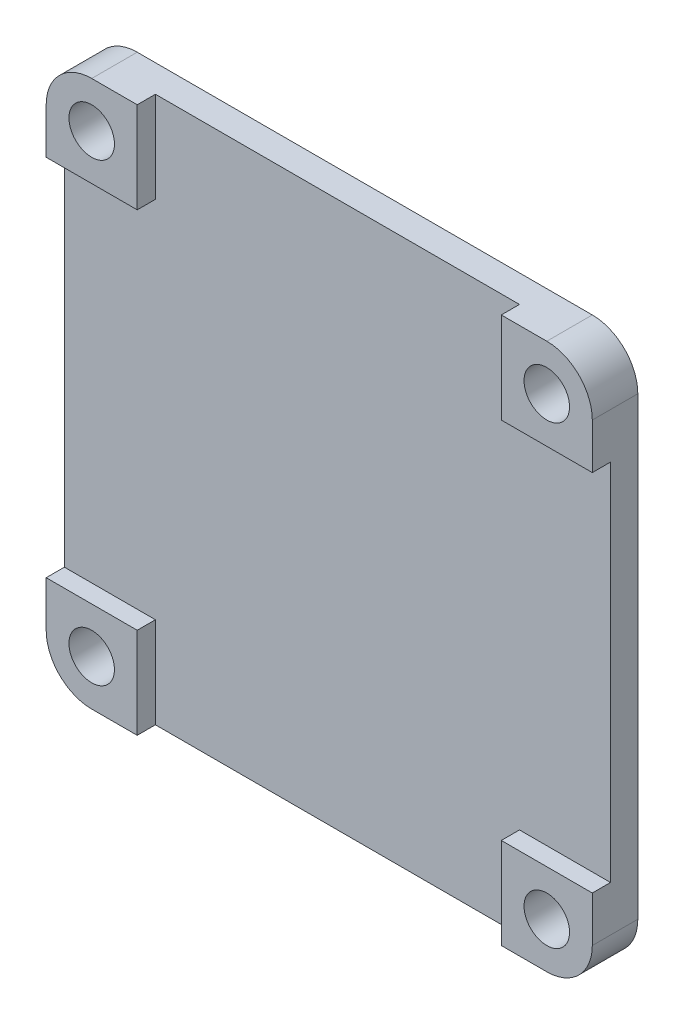
SolidWorks part; units mm, degrees
ref_plane "前视基准面" through (0, 0, 0) normal (0, 0, 1) x (1, 0, 0)
ref_plane "上视基准面" through (0, 0, 0) normal (0, 1, 0) x (1, 0, 0)
ref_plane "右视基准面" through (0, 0, 0) normal (1, 0, 0) x (0, 0, -1)
sketch "草图1" plane through (0, 0, 0) normal (0, 0, 1) x (1, 0, 0)
  line L0 (0, 0) -> (50.902, 0) construction
  line L1 (0, 0) -> (0, 39.4902) construction
  line L2 (-25, 30) -> (25, 30)
  line L3 (-30, 25) -> (-30, -25)
  line L4 (30, 25) -> (30, -25)
  line L5 (-25, -30) -> (25, -30)
  arc A0 (-25, 30) -> (-30, 25) centre (-25, 25) ccw
  circle A1 centre (-25, 25) radius 2.5
  circle A2 centre (25, 25) radius 2.5
  arc A3 (25, 30) -> (30, 25) centre (25, 25) cw
  arc A4 (25, -30) -> (30, -25) centre (25, -25) ccw
  circle A5 centre (25, -25) radius 2.5
  circle A6 centre (-25, -25) radius 2.5
  arc A7 (-25, -30) -> (-30, -25) centre (-25, -25) cw
  point P9 (0, -30)
  point P14 (-30, 0)
  point P15 (0, 30)
  point P23 (30, 0)
  dimension "D3" = 5
  dimension "D4" = 5
  dimension "D1" = 30
  dimension "D2" = 30
extrude "凸台-拉伸1" add sketch "草图1" along normal blind 3
sketch "草图2" plane through (0, 0, 3) normal (0, 0, 1) x (1, 0, 0)
  line L0 (0, 0) -> (46.7376, 0) construction
  line L1 (0, 0) -> (0, 23.4766) construction
  line L2 (-30, 25) -> (-30, 20)
  line L3 (-30, 25) -> (-30, -25) construction
  line L4 (-30, 20) -> (-20, 20)
  line L5 (-20, 20) -> (-20, 30)
  line L6 (25, 30) -> (-25, 30) construction
  line L7 (-20, 30) -> (-25, 30)
  line L8 (20, 30) -> (25, 30)
  line L9 (20, 20) -> (20, 30)
  line L10 (30, 20) -> (20, 20)
  line L11 (30, 25) -> (30, 20)
  line L12 (30, -25) -> (30, -20)
  line L13 (30, -20) -> (20, -20)
  line L14 (20, -20) -> (20, -30)
  line L15 (20, -30) -> (25, -30)
  line L16 (-20, -30) -> (-25, -30)
  line L17 (-20, -20) -> (-20, -30)
  line L18 (-30, -20) -> (-20, -20)
  line L19 (-30, -25) -> (-30, -20)
  arc A0 (-30, 25) -> (-25, 30) centre (-25, 25) cw
  circle A1 centre (-25, 25) radius 2.5
  circle A2 centre (25, 25) radius 2.5
  arc A3 (30, 25) -> (25, 30) centre (25, 25) ccw
  arc A4 (30, -25) -> (25, -30) centre (25, -25) cw
  circle A5 centre (25, -25) radius 2.5
  circle A6 centre (-25, -25) radius 2.5
  arc A7 (-30, -25) -> (-25, -30) centre (-25, -25) ccw
  dimension "D1" = 5
  dimension "D2" = 10
extrude "凸台-拉伸2" add sketch "草图2" along normal blind 2
sketch "草图3" plane through (0, 0, 0) normal (0, 0, -1) x (-1, 0, 0)
  line L0 (0, 0) -> (49.1095, 0) construction
  line L1 (0, 0) -> (0, 21.3742) construction
  line L2 (-13.5, 10) -> (-12, 10)
  line L3 (-12, 10) -> (-12, -10)
  line L4 (-13.5, 10) -> (-13.5, -10)
  line L5 (-13.5, -10) -> (-12, -10)
  line L6 (13.5, -10) -> (12, -10)
  line L7 (13.5, 10) -> (13.5, -10)
  line L8 (12, 10) -> (12, -10)
  line L9 (13.5, 10) -> (12, 10)
  point P9 (-13.5, 0)
  point P10 (-12, 0)
  dimension "D1" = 12
  dimension "D2" = 1.5
  dimension "D3" = 10
extrude "凸台-拉伸4" add sketch "草图3" along normal blind 3
sketch "草图5" plane through (0, 0, -3) normal (0, 0, -1) x (-1, 0, 0)
  line L1 (-13.5, 10) -> (-12, 10)
  line L2 (-13.5, 10) -> (-13.5, -10)
  line L3 (-13.5, -10) -> (-12, -10)
  line L4 (-12, 10) -> (-12, -10)
revolve "旋转2" add sketch "草图5" angle 90 about L4
sketch "草图6" plane through (12, 0, 0) normal (-1, 0, 0) x (0, 0, 1)
  line L0 (-4.5, 10) -> (0, 10) construction
  line L1 (-4.5, -10) -> (-3, -10)
  line L2 (-4.5, -10) -> (-4.5, 10)
  line L3 (-4.5, 10) -> (-3, 10)
  line L4 (-3, -10) -> (-3, 10)
  dimension "D1" = 1.5
extrude "凸台-拉伸5" add sketch "草图6" along normal blind 5
sketch "草图8" plane through (0, 0, -3) normal (0, 0, -1) x (-1, 0, 0)
  line L1 (13.5, 10) -> (12, 10)
  line L2 (13.5, 10) -> (13.5, -10)
  line L3 (13.5, -10) -> (12, -10)
  line L4 (12, 10) -> (12, -10)
revolve "旋转3" add sketch "草图8" angle 90 about L4
sketch "草图9" plane through (-12, 0, 0) normal (1, 0, 0) x (0, 0, -1)
  line L0 (4.5, -10) -> (0, -10) construction
  line L1 (4.5, 10) -> (3, 10)
  line L2 (4.5, 10) -> (4.5, -10)
  line L3 (4.5, -10) -> (3, -10)
  line L4 (3, 10) -> (3, -10)
  dimension "D1" = 1.5
extrude "凸台-拉伸6" add sketch "草图9" along normal blind 5
